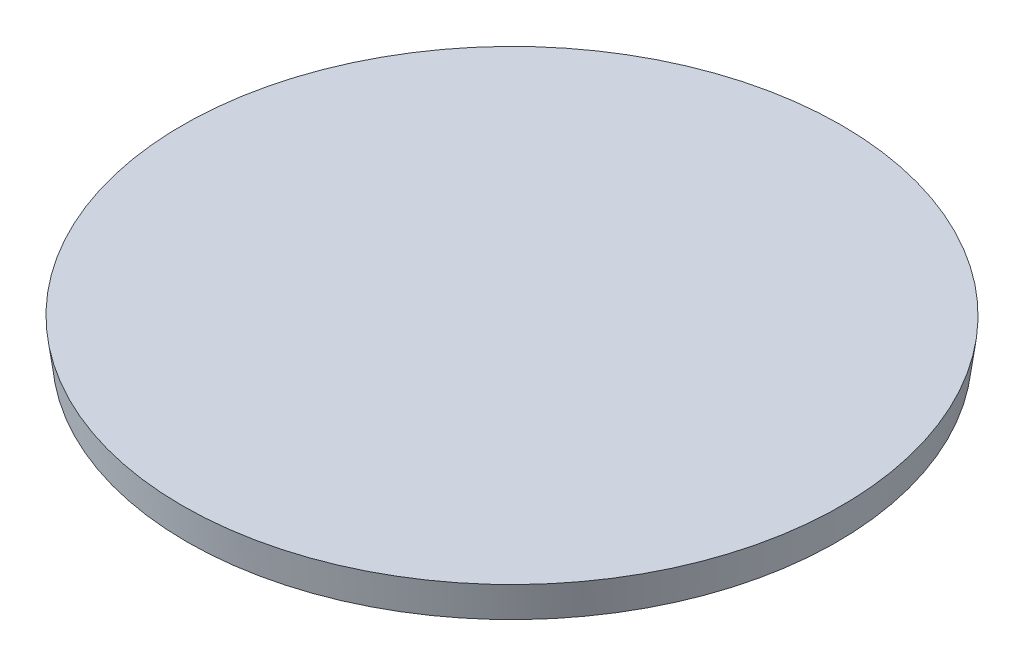
SolidWorks part; units mm, degrees
ref_plane "Front Plane" through (0, 0, 0) normal (0, 0, 1) x (1, 0, 0)
ref_plane "Top Plane" through (0, 0, 0) normal (0, 1, 0) x (1, 0, 0)
ref_plane "Right Plane" through (0, 0, 0) normal (1, 0, 0) x (0, 0, -1)
sketch "Sketch2" plane through (0, 0, 0) normal (0, 0, 1) x (1, 0, 0)
  line L0 (0, 0) -> (14.7955, 0)
  line L1 (14.7955, 0) -> (14.9961, 1.524)
  line L2 (14.9961, 1.524) -> (0, 1.524)
  line L4 (0, 1.524) -> (0, 0) construction
  line L5 (0, 1.524) -> (0, 0)
  dimension "D1" = 1.524
  dimension "D2" = 29.591
  dimension "D3" = 7.5
revolve "Revolve1" add sketch "Sketch2" angle 360 about L4
